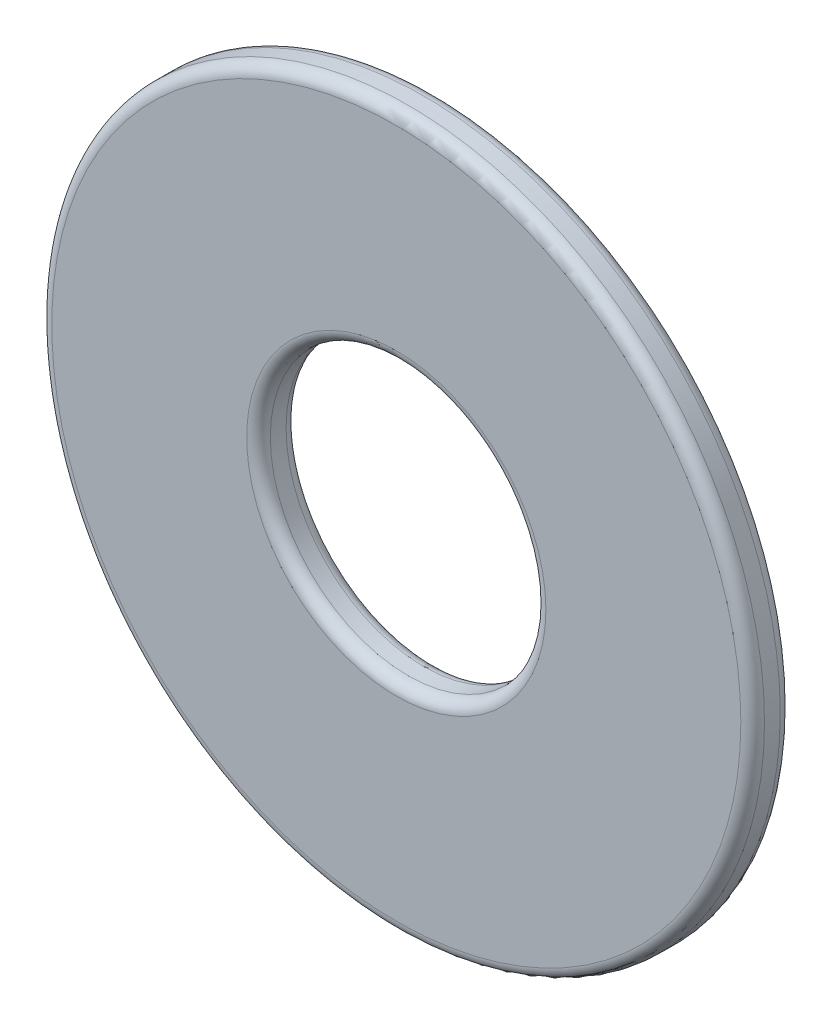
SolidWorks part; units mm, degrees
ref_plane "Plano frontal" through (0, 0, 0) normal (0, 0, 1) x (1, 0, 0)
ref_plane "Plano superior" through (0, 0, 0) normal (0, 1, 0) x (1, 0, 0)
ref_plane "Plano direito" through (0, 0, 0) normal (1, 0, 0) x (0, 0, -1)
sketch "Esboço1" plane through (0, 0, 0) normal (0, 0, 1) x (1, 0, 0)
  circle A0 centre (0, 0) radius 3.5
  circle A1 centre (0, 0) radius 9.05
  dimension "D1" = 7
  dimension "D2" = 18.1
extrude "Ressalto-extrusão1" add sketch "Esboço1" along normal blind 1
fillet "Filete1" radius 0.3 4 edges at (3.5, 0, 0) (9.05, 0, 0) (3.5, 0, 1) (9.05, 0, 1)
